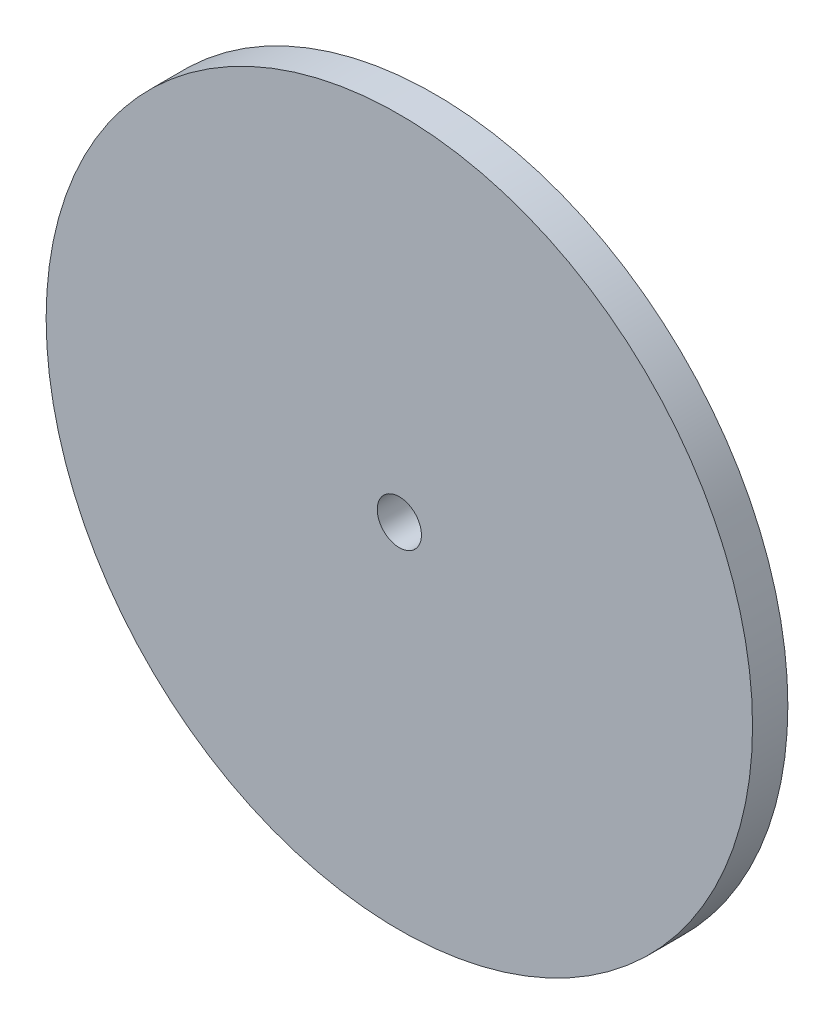
SolidWorks part; units mm, degrees
ref_plane "Plan de face" through (0, 0, 0) normal (0, 0, 1) x (1, 0, 0)
ref_plane "Plan de dessus" through (0, 0, 0) normal (0, 1, 0) x (1, 0, 0)
ref_plane "Plan de droite" through (0, 0, 0) normal (1, 0, 0) x (0, 0, -1)
sketch "Esquisse1" plane through (0, 0, 0) normal (0, 0, 1) x (1, 0, 0)
  circle A0 centre (0, 0) radius 40
  dimension "D1" = 80
extrude "Boss.-Extru.1" add sketch "Esquisse1" along normal blind 4
sketch "Esquisse2" plane through (0, 0, 4) normal (0, 0, 1) x (1, 0, 0)
  circle A0 centre (0, 0) radius 2.5
  dimension "D1" = 5
extrude "Enlèv. mat.-Extru.1" cut sketch "Esquisse2" against normal through all
